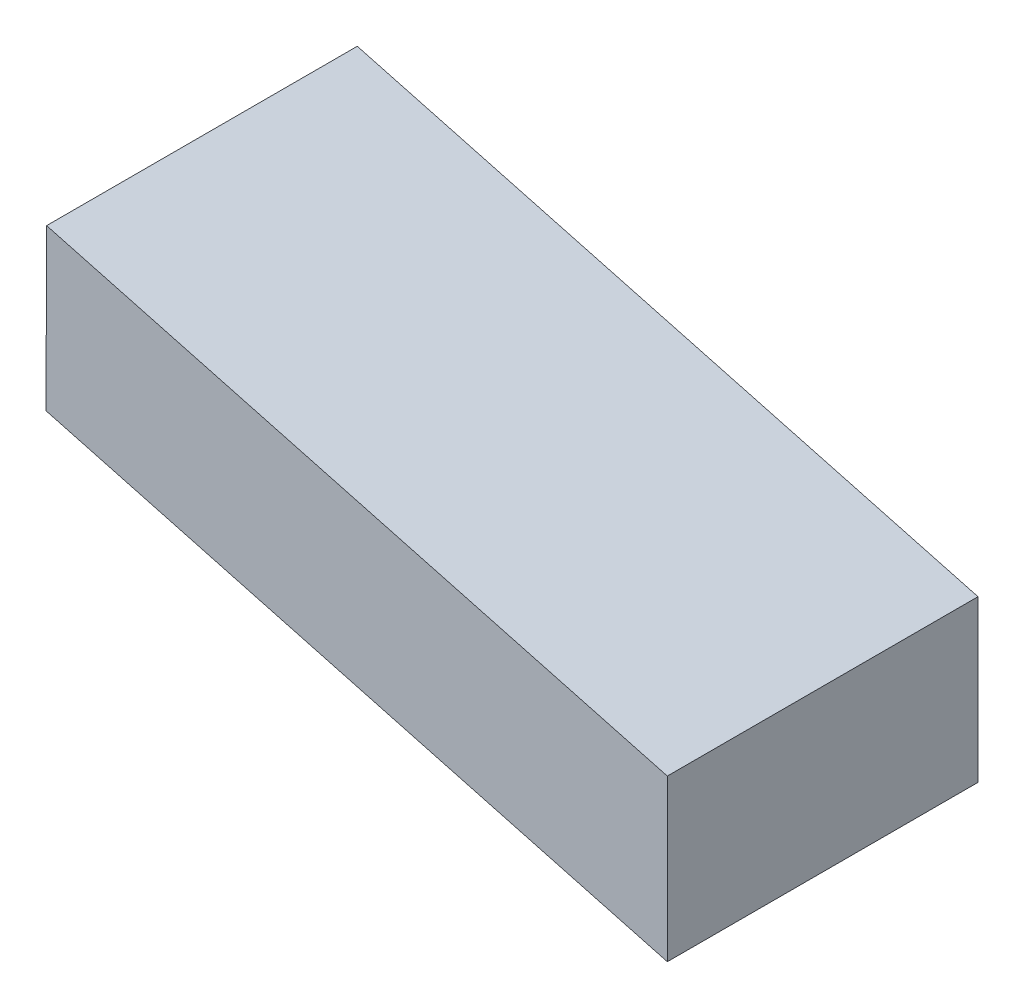
SolidWorks part; units mm, degrees
material "ABS"
ref_plane "Спереди" through (0, 0, 0) normal (0, 0, 1) x (1, 0, 0)
ref_plane "Сверху" through (0, 0, 0) normal (0, 1, 0) x (1, 0, 0)
ref_plane "Справа" through (0, 0, 0) normal (1, 0, 0) x (0, 0, -1)
sketch "Эскиз1" plane through (0, 0, 0) normal (0, 0, 1) x (1, 0, 0)
  line L0 (0, 0) -> (0, 5.1764)
  line L1 (0, 0) -> (-20, 5.359)
  line L2 (0, 5.1764) -> (-19.9803, 10.5301)
  line L3 (-19.9803, 10.5301) -> (-20, 5.359)
  line L4 (0, 0) -> (-89.8359, 0) construction
  point P5 (-20, 10.5301)
  dimension "D1" = 15
  dimension "D2" = 20
  dimension "D3" = 5
extrude "Бобышка-Вытянуть1" add sketch "Эскиз1" against normal blind 10
